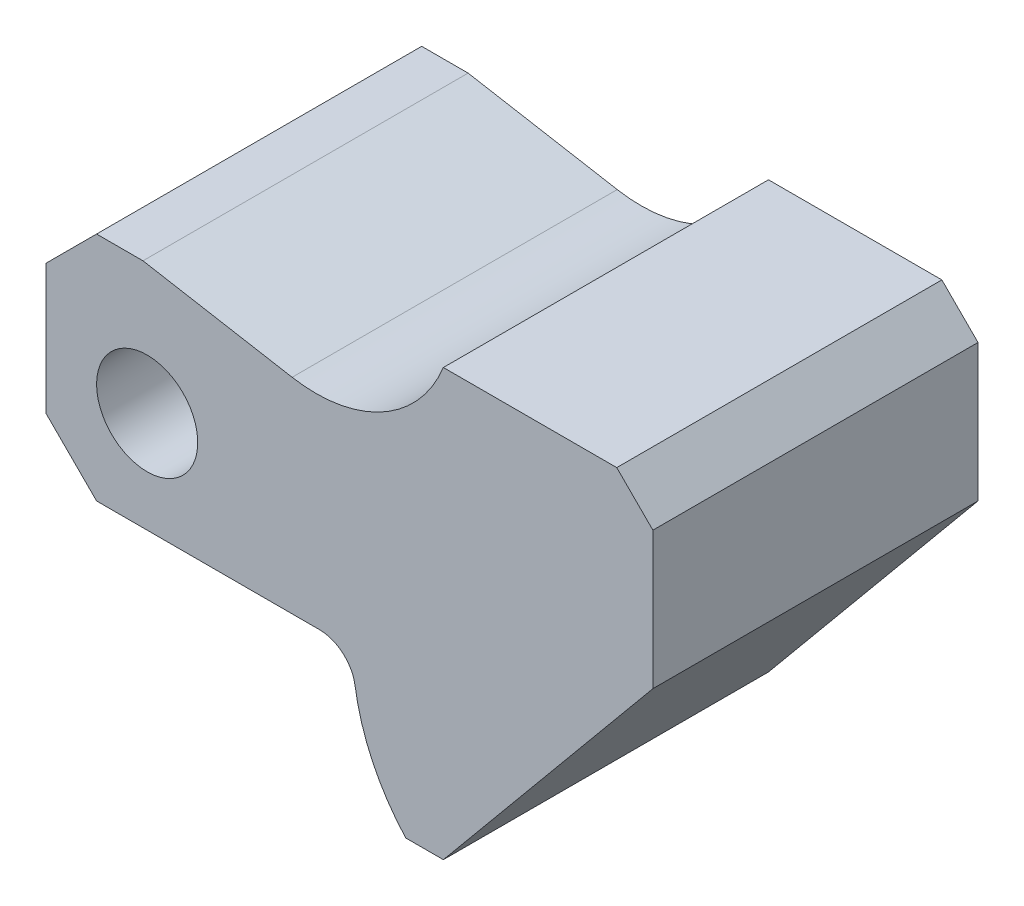
SolidWorks part; units mm, degrees
material "AISI 1020"
ref_plane "Front Plane" through (0, 0, 0) normal (0, 0, 1) x (1, 0, 0)
ref_plane "Top Plane" through (0, 0, 0) normal (0, 1, 0) x (1, 0, 0)
ref_plane "Right Plane" through (0, 0, 0) normal (1, 0, 0) x (0, 0, -1)
sketch "Sketch1" plane through (0, 0, 0) normal (0, 0, 1) x (1, 0, 0)
  line L0 (0, 0) -> (-7, 7)
  line L1 (-7, 7) -> (-7, 25)
  line L2 (-7, 25) -> (0, 32)
  line L3 (0, 32) -> (6.4231, 32)
  line L4 (48, 40) -> (72, 40)
  line L5 (72, 40) -> (77, 35)
  line L6 (77, 35) -> (77, 16)
  line L7 (77, 16) -> (48, -19)
  line L8 (48, -19) -> (42.7881, -19)
  line L10 (30.8344, 0) -> (0, 0)
  line L11 (-7, 14) -> (7, 14) construction
  line L12 (63.7429, -19) -> (63.7429, 0) construction
  line L13 (6.4231, 32) -> (16.9623, 32) construction
  line L14 (6.4231, 32) -> (27.0657, 28.3602)
  circle A0 centre (7, 14) radius 7
  arc A1 (35.7777, -4.2489) -> (30.8344, 0) centre (30.8344, -5) ccw
  arc A2 (42.7881, -19) -> (35.7777, -4.2489) centre (63.7429, 0) cw
  arc A3 (48, 40) -> (27.0657, 28.3602) centre (30.365, 47.0715) cw
  point P18 (0, 0)
  point P23 (22.0705, 29.2409)
  point P25 (0, 0)
  point P26 (63.7429, 0)
  dimension "D5" = 45
  dimension "D17" = 5
  dimension "D20" = 10
  dimension "D21" = 19
  dimension "D1" = 7
  dimension "D2" = 32
  dimension "D3" = 14
  dimension "D4" = 14
  dimension "D6" = 19
  dimension "D7" = 14
  dimension "D8" = 7
  dimension "D9" = 45
  dimension "D10" = 14
  dimension "D11" = 29
  dimension "D12" = 45
  dimension "D13" = 5
  dimension "D14" = 24
  dimension "D15" = 84
  dimension "D16" = 59
  dimension "D18" = 19
  dimension "D19" = 29
extrude "Boss-Extrude1" add sketch "Sketch1" along normal blind 45
